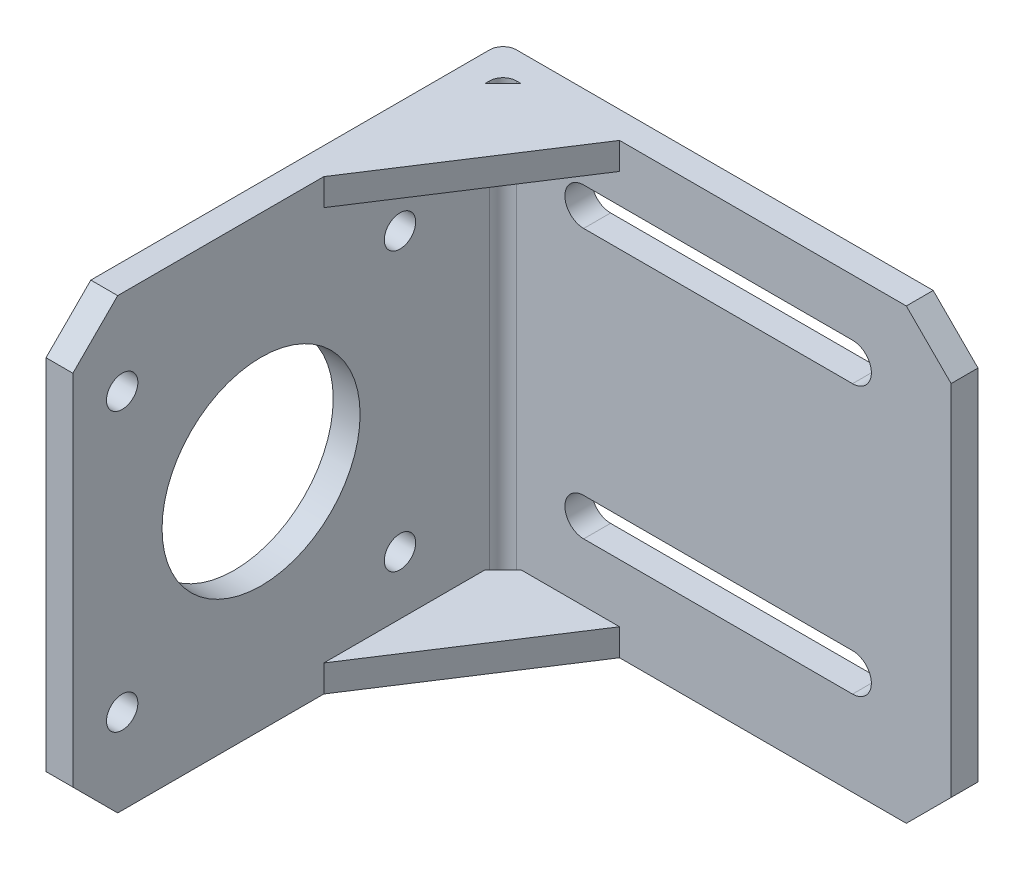
SolidWorks part; units mm, degrees
ref_plane "Plan de face" through (0, 0, 0) normal (0, 0, 1) x (1, 0, 0)
ref_plane "Plan de dessus" through (0, 0, 0) normal (0, 1, 0) x (1, 0, 0)
ref_plane "Plan de droite" through (0, 0, 0) normal (1, 0, 0) x (0, 0, -1)
sketch "Esquisse1" plane through (0, 0, 0) normal (0, 0, 1) x (1, 0, 0)
  line L1 (27.037, 0) -> (80.037, 0)
  line L2 (27.037, 0) -> (27.037, -50)
  line L3 (27.037, -50) -> (80.037, -50)
  line L4 (80.037, 0) -> (80.037, -50)
  line L5 (39.037, -6.3084) -> (69.037, -6.3084)
  line L6 (39.037, -6.3084) -> (39.037, -10.5084)
  line L7 (39.037, -10.5084) -> (69.037, -10.5084)
  line L8 (69.037, -6.3084) -> (69.037, -10.5084)
  line L9 (39.037, -36.3084) -> (69.037, -36.3084)
  line L10 (39.037, -36.3084) -> (39.037, -40.5084)
  line L11 (39.037, -40.5084) -> (69.037, -40.5084)
  line L12 (69.037, -36.3084) -> (69.037, -40.5084)
  arc A0 (69.037, -6.3084) -> (69.037, -10.5084) centre (69.037, -8.4084) cw
  arc A1 (39.037, -10.5084) -> (39.037, -6.3084) centre (39.037, -8.4084) cw
  arc A2 (39.037, -36.3084) -> (39.037, -40.5084) centre (39.037, -38.4084) ccw
  arc A3 (69.037, -36.3084) -> (69.037, -40.5084) centre (69.037, -38.4084) cw
  point P12 (69.037, -8.4084)
  point P13 (69.037, -38.4084)
  point P14 (39.037, -8.4084)
  point P15 (39.037, -38.4084)
  dimension "D1" = 50
  dimension "D2" = 53
  dimension "D3" = 4.2
  dimension "D4" = 4.2
  dimension "D5" = 30
  dimension "D6" = 30
  dimension "D7" = 30
  dimension "D8" = 11
  dimension "D9" = 11
extrude "Boss.-Extru.1" add sketch "Esquisse1" along normal blind 3 contours L4 L1 L2 L3 L7 A1 L5 A0 L9 A3 L11 A2
sketch "Esquisse2" plane through (0, 0, 3) normal (0, 0, 1) x (1, 0, 0)
  line L0 (27.037, -50) -> (80.037, -50) construction
  line L1 (27.037, 0) -> (30.037, 0)
  line L2 (27.037, 0) -> (27.037, -50)
  line L3 (27.037, -50) -> (30.037, -50)
  line L4 (30.037, 0) -> (30.037, -50)
  dimension "D1" = 3
extrude "Boss.-Extru.2" add sketch "Esquisse2" along normal blind 48
sketch "Esquisse3" plane through (27.037, 0, 0) normal (-1, 0, 0) x (0, 0, 1)
  line L0 (51, 0) -> (51, -50) construction
  line L1 (51, 0) -> (0, 0) construction
  line L2 (51, -50) -> (0, -50) construction
  circle A0 centre (30, -25) radius 11.05
  circle A1 centre (14.5, -9.5) radius 1.75
  circle A2 centre (45.5, -9.5) radius 1.75
  circle A3 centre (45.5, -40.5) radius 1.75
  circle A4 centre (14.5, -40.5) radius 1.75
  dimension "D1" = 22.1
  dimension "D2" = 3.5
  dimension "D3" = 3.5
  dimension "D4" = 3.5
  dimension "D5" = 3.5
  dimension "D6" = 31
  dimension "D7" = 31
  dimension "D8" = 31
  dimension "D9" = 31
  dimension "D10" = 21
  dimension "D11" = 50
  dimension "D12" = 25
  dimension "D13" = 9.5
  dimension "D14" = 9.5
  dimension "D15" = 9.5
  dimension "D16" = 9.5
  dimension "D17" = 15.5
  dimension "D18" = 15.5
extrude "Enlèv. mat.-Extru.1" cut sketch "Esquisse3" against normal blind 49
chamfer "Chanfrein1" distance 5 angle 45 4 edges at (28.537, -50, 51) (28.537, 0, 51) (80.037, 0, 1.5) (80.037, -50, 1.5)
sketch "Esquisse4" plane through (0, -50, 0) normal (0, -1, 0) x (1, 0, 0)
  line L0 (30.037, 3) -> (43.037, 3)
  line L1 (30.037, 3) -> (75.037, 3) construction
  line L2 (43.037, 3) -> (30.037, 23)
  line L3 (30.037, 46) -> (30.037, 3) construction
  line L4 (30.037, 23) -> (30.037, 3)
  line L5 (30.037, 5) -> (32.037, 3)
  line M7 (75.037, 3) -> (30.037, 3)
  dimension "D1" = 20
  dimension "D2" = 13
  dimension "D3" = 2
  dimension "D4" = 2
extrude "Boss.-Extru.3" add sketch "Esquisse4" against normal blind 3 contours L4 L5 L2 M7
pattern_linear "Répétition linéaire1" count 2 spacing 47 along (0, 1, 0) of "Boss.-Extru.3"
fillet "Congé3" radius 1.5 2 edges at (27.037, -25, 0) (30.037, -25, 3)
